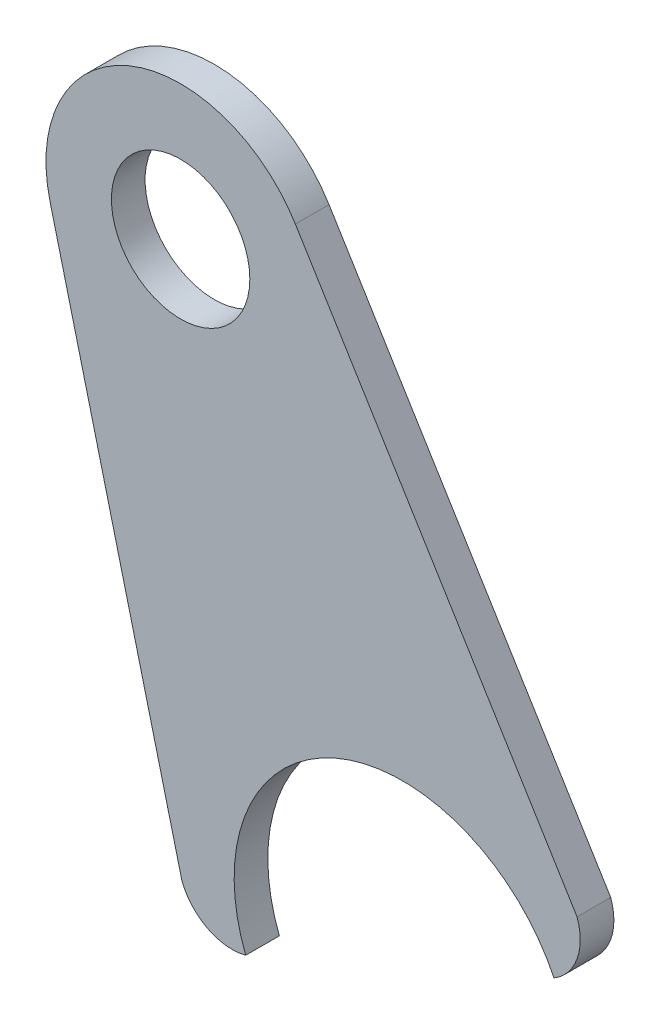
SolidWorks part; units mm, degrees
ref_plane "Front Plane" through (0, 0, 0) normal (0, 0, 1) x (1, 0, 0)
ref_plane "Top Plane" through (0, 0, 0) normal (0, 1, 0) x (1, 0, 0)
ref_plane "Right Plane" through (0, 0, 0) normal (1, 0, 0) x (0, 0, -1)
sketch "Sketch1" plane through (0, 0, 0) normal (0, 0, 1) x (1, 0, 0)
  line L5 (7.1468, 3.4535) -> (-7.3933, -2.8886) construction
  line L8 (-10.3992, -1.3553) -> (-16.6189, 23.2714)
  line L9 (8.2327, 6.4965) -> (-5.0496, 28.1469)
  arc A2 (7.1468, 3.4535) -> (8.2327, 6.4965) centre (5.8437, 5.6337) ccw
  arc A3 (7.1468, 3.4535) -> (-7.3933, -2.8886) centre (0, 0) ccw
  arc A4 (-16.6189, 23.2714) -> (-5.0496, 28.1469) centre (-10.4622, 24.8263) cw
  arc A5 (-7.3933, -2.8886) -> (-10.3992, -1.3553) centre (-8.0335, -0.4306) cw
  circle A6 centre (-10.4622, 24.8263) radius 3.2639
  dimension "D1" = 6.35
  dimension "D2" = 15.875
  dimension "D3" = 2.54
  dimension "D4" = 2.54
  dimension "D7" = 6.5278
  dimension "D5" = 25.4
  dimension "D6" = 25.4
extrude "Boss-Extrude1" add sketch "Sketch1" along normal blind 1.5875
